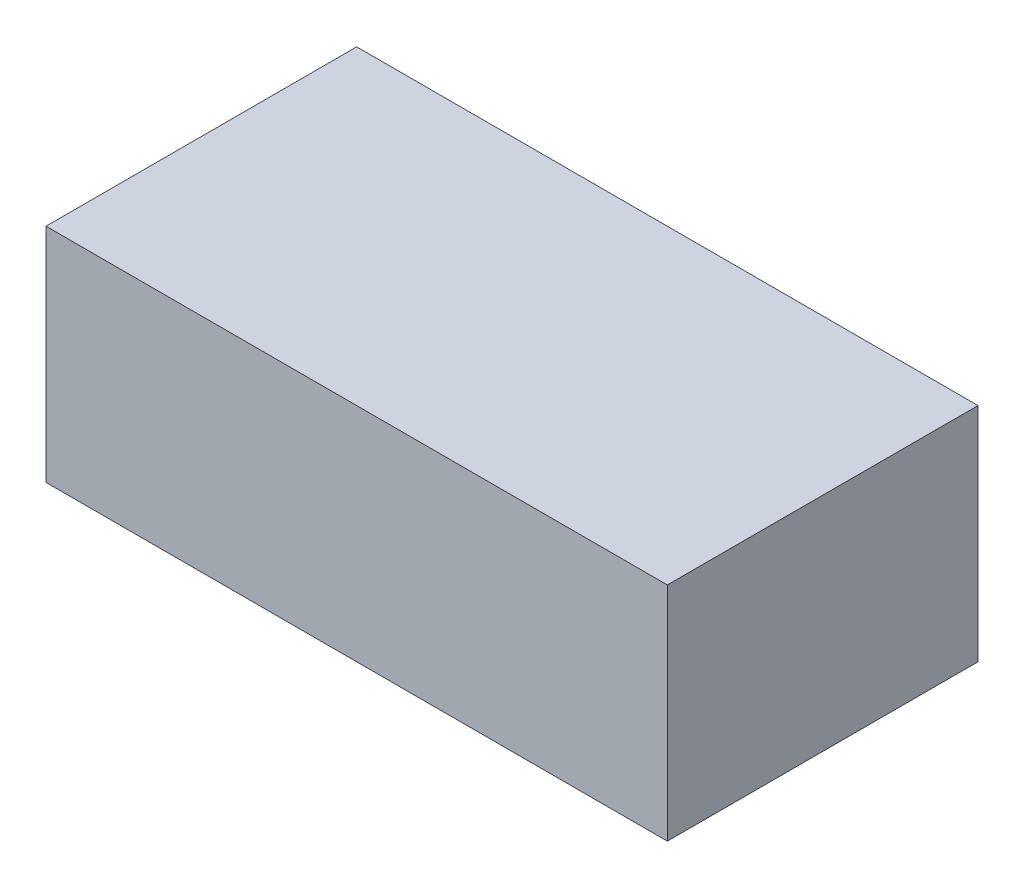
SolidWorks part; units mm, degrees
ref_plane "Front" through (0, 0, 0) normal (0, 0, 1) x (1, 0, 0)
ref_plane "Top" through (0, 0, 0) normal (0, 1, 0) x (1, 0, 0)
ref_plane "Right" through (0, 0, 0) normal (1, 0, 0) x (0, 0, -1)
sketch "Sketch1" plane through (0, 0, 0) normal (0, 1, 0) x (1, 0, 0)
  line L1 (-70, -35) -> (70, -35)
  line L2 (-70, -35) -> (-70, 35)
  line L3 (-70, 35) -> (70, 35)
  line L4 (70, -35) -> (70, 35)
  line L5 (-70, -35) -> (70, 35) construction
  line L6 (-70, 35) -> (70, -35) construction
  point P0 (0, 0)
  dimension "D1" = 70
  dimension "D2" = 140
extrude "Boss-Extrude1" add sketch "Sketch1" along normal blind 50
shell "Shell1" thickness 2
